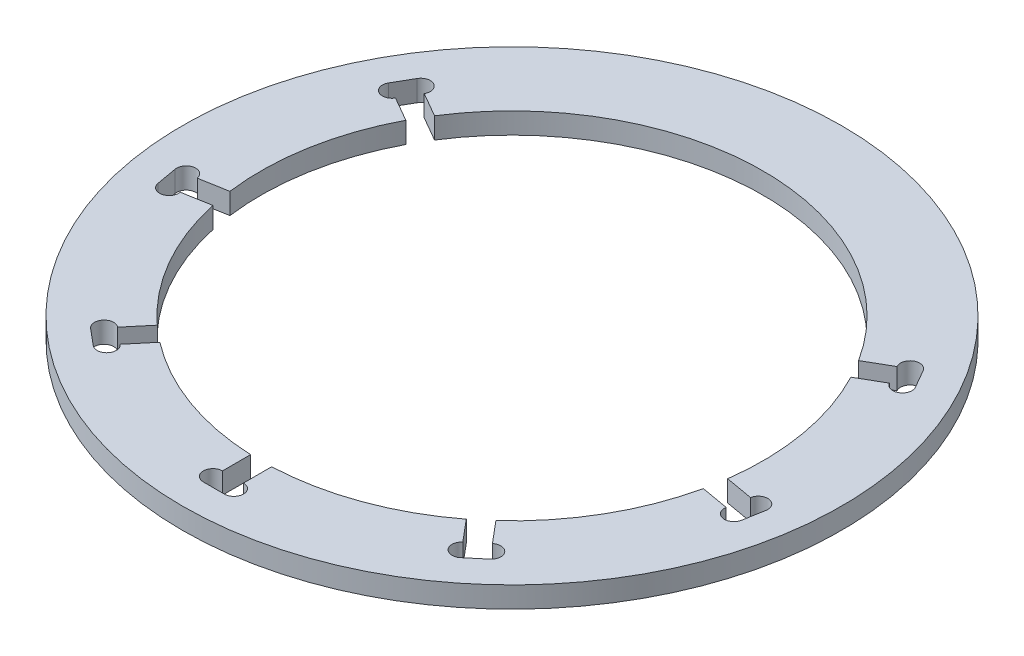
SolidWorks part; units mm, degrees
material "Balsa"
ref_plane "Front Plane" through (0, 0, 0) normal (0, 0, 1) x (1, 0, 0)
ref_plane "Top Plane" through (0, 0, 0) normal (0, 1, 0) x (1, 0, 0)
ref_plane "Right Plane" through (0, 0, 0) normal (1, 0, 0) x (0, 0, -1)
sketch "Sketch1" plane through (0, 0, 0) normal (0, 1, 0) x (1, 0, 0)
  circle A0 centre (0, 0) radius 105
  circle A1 centre (0, 0) radius 80
  dimension "D1" = 105
  dimension "D2" = 80
extrude "Boss-Extrude1" add sketch "Sketch1" along normal blind 6.7 contours A0
sketch "Sketch2" plane through (0, 6.7, 0) normal (0, 1, 0) x (1, 0, 0)
  line L0 (0, 0) -> (90.9327, 52.5) construction
  line L1 (74.4423, -9.7245) -> (88.1311, -12.1382)
  line L2 (63.2769, 40.4012) -> (75.3147, 47.3512)
  line L3 (63.2769, 40.4012) -> (66.6269, 34.5988)
  line L4 (66.6269, 34.5988) -> (78.6647, 41.5488)
  line L5 (80.5974, 50.4012) -> (83.9474, 44.5988)
  line L6 (73.2789, -16.3227) -> (86.9677, -18.7364)
  line L7 (74.4423, -9.7245) -> (73.2789, -16.3227)
  line L8 (94.1385, -13.1975) -> (92.975, -19.7957)
  line L9 (50.7753, -55.3) -> (59.7101, -65.948)
  line L10 (45.6428, -59.6067) -> (54.5776, -70.2547)
  line L11 (50.7753, -55.3) -> (45.6428, -59.6067)
  line L12 (63.6311, -70.6209) -> (58.4986, -74.9276)
  line L13 (3.35, -75) -> (3.35, -88.9)
  line L14 (-3.35, -75) -> (-3.35, -88.9)
  line L15 (3.35, -75) -> (-3.35, -75)
  line L16 (3.35, -95) -> (-3.35, -95)
  line L17 (-45.6428, -59.6067) -> (-54.5776, -70.2547)
  line L18 (-50.7753, -55.3) -> (-59.7101, -65.948)
  line L19 (-45.6428, -59.6067) -> (-50.7753, -55.3)
  line L20 (-58.4986, -74.9276) -> (-63.6311, -70.6209)
  line L21 (-73.2789, -16.3227) -> (-86.9677, -18.7364)
  line L22 (-74.4423, -9.7245) -> (-88.1311, -12.1382)
  line L23 (-73.2789, -16.3227) -> (-74.4423, -9.7245)
  line L24 (-92.975, -19.7957) -> (-94.1385, -13.1975)
  line L25 (-66.6269, 34.5988) -> (-78.6647, 41.5488)
  line L26 (-63.2769, 40.4012) -> (-75.3147, 47.3512)
  line L27 (-66.6269, 34.5988) -> (-63.2769, 40.4012)
  line L28 (-83.9474, 44.5988) -> (-80.5974, 50.4012)
  line L63 (0, 0) -> (0, 102.8222) construction
  circle A0 centre (0, 0) radius 105 construction
  circle A1 centre (0, -10) radius 3.5
  arc A2 (83.9474, 44.5988) -> (78.6647, 41.5488) centre (81.306, 43.0738) cw
  arc A3 (80.5974, 50.4012) -> (75.3147, 47.3512) centre (77.956, 48.8762) ccw
  arc A4 (94.1385, -13.1975) -> (88.1311, -12.1382) centre (91.1348, -12.6678) ccw
  arc A5 (92.975, -19.7957) -> (86.9677, -18.7364) centre (89.9714, -19.2661) cw
  arc A6 (63.6311, -70.6209) -> (59.7101, -65.948) centre (61.6706, -68.2844) ccw
  arc A7 (58.4986, -74.9276) -> (54.5776, -70.2547) centre (56.5381, -72.5911) cw
  arc A8 (3.35, -95) -> (3.35, -88.9) centre (3.35, -91.95) ccw
  arc A9 (-3.35, -95) -> (-3.35, -88.9) centre (-3.35, -91.95) cw
  arc A10 (-58.4986, -74.9276) -> (-54.5776, -70.2547) centre (-56.5381, -72.5911) ccw
  arc A11 (-63.6311, -70.6209) -> (-59.7101, -65.948) centre (-61.6706, -68.2844) cw
  arc A12 (-92.975, -19.7957) -> (-86.9677, -18.7364) centre (-89.9714, -19.2661) ccw
  arc A13 (-94.1385, -13.1975) -> (-88.1311, -12.1382) centre (-91.1348, -12.6678) cw
  arc A14 (-83.9474, 44.5988) -> (-78.6647, 41.5488) centre (-81.306, 43.0738) ccw
  arc A15 (-80.5974, 50.4012) -> (-75.3147, 47.3512) centre (-77.956, 48.8762) cw
  point P13 (-12.0777, 27.2748)
  point P75 (64.9519, 37.5)
  dimension "D9" = 7
  dimension "D5" = 3.05
  dimension "D1" = 20
  dimension "D2" = 6.7
  dimension "D3" = 3.35
  dimension "D10" = 10
  dimension "D4" = 75
  dimension "D7" = 7
extrude "Cut-Extrude3" cut sketch "Sketch2" against normal blind 6.7
equation "\"Ring inner radius\"= 80mm"
equation "\"D1@Sketch1\" = \"Ring outer radius\""
equation "\"Heart cable hole radius\"= 3.5mm"
equation "\"Dogbone radius\"= 3.05mm"
equation "\"Tree side stock thickness\"= 6.7mm"
equation "\"D2@Sketch2\"= \"Tree side stock thickness\""
equation "\"D3@Sketch2\"= \"Tree side stock thickness\" / 2"
equation "\"Ring stock thickness\"= 6.7mm"
equation "\"D1@Boss-Extrude1\"= \"Ring stock thickness\""
equation "\"D1@Cut-Extrude3\"= \"Ring stock thickness\""
equation "\"Tree teeth\"= 15mm"
equation "\"Tree slot\"= 15mm"
equation "\"D1@Sketch2\"= \"Tree slot\" + \"Cut-Extrude Tolerance\""
equation "\"Bottom ring outer radius\"= \"Ring inner radius\" + \"Tree teeth\""
equation "\"D4@Sketch2\" = \"Ring inner radius\" - \"Cut-Extrude Tolerance\""
equation "\"D9@Sketch2\" = \"Heart cable hole radius\" * 2"
equation "\"Cut-Extrude Tolerance\"= 5mm"
equation "\"Ring outer radius\"= \"Ring inner radius\" + \"Tree slot\" + 10"
equation "\"D2@Sketch1\"= \"Ring inner radius\""
equation "\"D5@Sketch2\"=\"Dogbone radius\""
